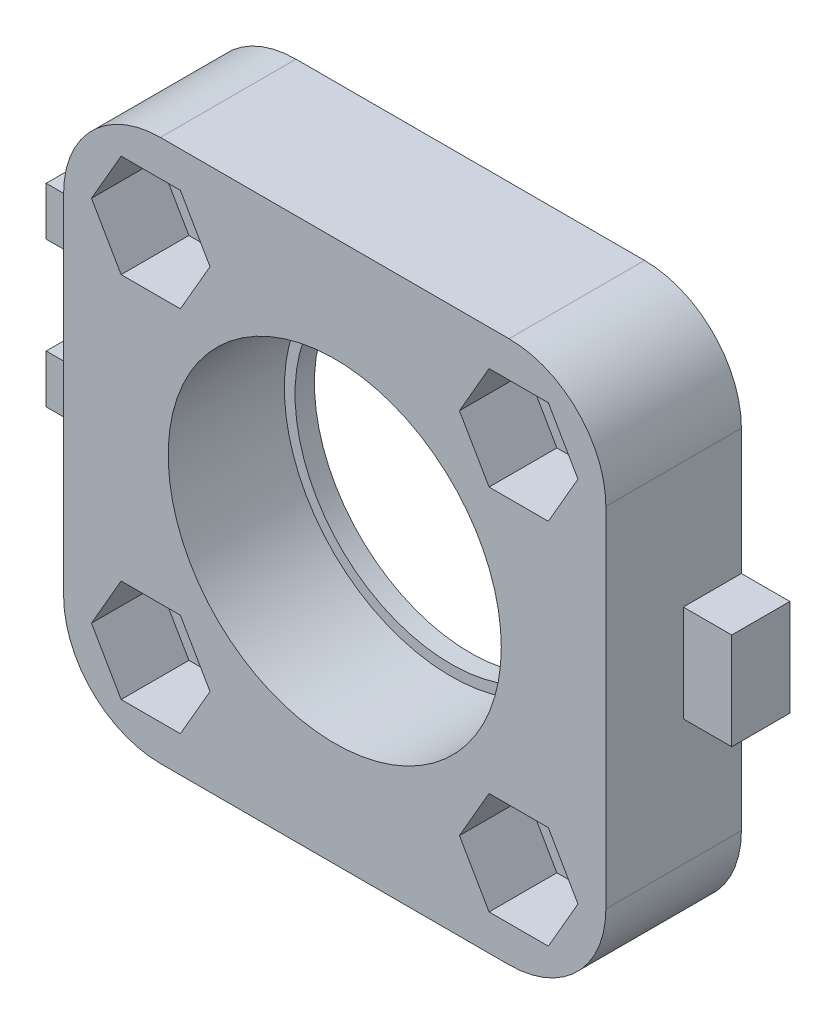
SolidWorks part; units mm, degrees
ref_plane "Alzado" through (0, 0, 0) normal (0, 0, 1) x (1, 0, 0)
ref_plane "Planta" through (0, 0, 0) normal (0, 1, 0) x (1, 0, 0)
ref_plane "Vista lateral" through (0, 0, 0) normal (1, 0, 0) x (0, 0, -1)
sketch "Croquis1" plane through (0, 0, 0) normal (0, 0, 1) x (1, 0, 0)
  line L1 (-14, -14) -> (14, -14)
  line L2 (-14, -14) -> (-14, 14)
  line L3 (-14, 14) -> (14, 14)
  line L4 (14, -14) -> (14, 14)
  line L5 (-14, -14) -> (14, 14) construction
  line L6 (-14, 14) -> (14, -14) construction
  circle A0 centre (0, 0) radius 8.05
  dimension "D1" = 16.1
  dimension "D2" = 28
  dimension "D3" = 28
extrude "Saliente-Extruir1" add sketch "Croquis1" along normal mid plane 1
sketch "Croquis2" plane through (0, 0, 0.5) normal (0, 0, 1) x (1, 0, 0)
  line L4 (14, -14) -> (14, 14)
  line L5 (14, 14) -> (-14, 14)
  line L6 (-14, 14) -> (-14, -14)
  line L7 (-14, -14) -> (14, -14)
  line L8 (14, -14) -> (14, 14)
  line L9 (14, 14) -> (-14, 14)
  line L10 (-14, 14) -> (-14, -14)
  line L11 (-14, -14) -> (14, -14)
  circle A0 centre (0, 0) radius 8.6
  dimension "D2" = 17.2
  dimension "D1" = 0
extrude "Saliente-Extruir2" add sketch "Croquis2" along normal blind 6
sketch "Croquis3" plane through (0, 0, 6.5) normal (0, 0, 1) x (1, 0, 0)
  line L0 (-9.5, 9.5) -> (9.5, 9.5) construction
  line L1 (9.5, 9.5) -> (9.5, -9.5) construction
  line L2 (9.5, -9.5) -> (-9.5, -9.5) construction
  line L3 (-9.5, -9.5) -> (-9.5, 9.5) construction
  line L5 (0, 13.0603) -> (0, -13.8489) construction
  line L6 (15.5492, 0) -> (-17.9148, 0) construction
  line L7 (11.03, 12.15) -> (7.97, 12.15)
  line L8 (-6.44, 9.5) -> (-7.97, 12.15)
  line L9 (-7.97, 12.15) -> (-11.03, 12.15)
  line L10 (-11.03, 12.15) -> (-12.56, 9.5)
  line L11 (-12.56, 9.5) -> (-11.03, 6.85)
  line L12 (-11.03, 6.85) -> (-7.97, 6.85)
  line L13 (-7.97, 6.85) -> (-6.44, 9.5)
  line L14 (7.97, 12.15) -> (6.44, 9.5)
  line L15 (6.44, 9.5) -> (7.97, 6.85)
  line L16 (7.97, 6.85) -> (11.03, 6.85)
  line L17 (11.03, 6.85) -> (12.56, 9.5)
  line L18 (12.56, 9.5) -> (11.03, 12.15)
  line L19 (-7.97, -6.85) -> (-11.03, -6.85)
  line L20 (-11.03, -6.85) -> (-12.56, -9.5)
  line L21 (-12.56, -9.5) -> (-11.03, -12.15)
  line L22 (-11.03, -12.15) -> (-7.97, -12.15)
  line L23 (-7.97, -12.15) -> (-6.44, -9.5)
  line L24 (-6.44, -9.5) -> (-7.97, -6.85)
  line L25 (11.03, -6.85) -> (7.97, -6.85)
  line L26 (7.97, -6.85) -> (6.44, -9.5)
  line L27 (6.44, -9.5) -> (7.97, -12.15)
  line L28 (7.97, -12.15) -> (11.03, -12.15)
  line L29 (11.03, -12.15) -> (12.56, -9.5)
  line L30 (12.56, -9.5) -> (11.03, -6.85)
  circle A0 centre (-9.5, 9.5) radius 1.5 construction
  circle A1 centre (-9.5, -9.5) radius 1.5 construction
  circle A2 centre (9.5, -9.5) radius 1.5 construction
  circle A3 centre (9.5, 9.5) radius 1.5 construction
  circle A4 centre (-9.5, 9.5) radius 2.65 construction
  circle A5 centre (9.5, 9.5) radius 2.65 construction
  circle A6 centre (-9.5, -9.5) radius 2.65 construction
  circle A7 centre (9.5, -9.5) radius 2.65 construction
  point P13 (0, -9.5)
  point P14 (-9.5, 0)
  dimension "D1" = 3
  dimension "D2" = 19
  dimension "D3" = 19
  dimension "D4" = 5.3
extrude "Cortar-Extruir1" cut sketch "Croquis3" against normal blind 3.5
sketch "Croquis6" plane through (0, 0, -0.5) normal (0, 0, -1) x (-1, 0, 0)
  line L0 (-9.5, 9.5) -> (9.5, 9.5) construction
  line L1 (9.5, 9.5) -> (9.5, -9.5) construction
  line L2 (9.5, -9.5) -> (-9.5, -9.5) construction
  line L3 (-9.5, -9.5) -> (-9.5, 9.5) construction
  line L4 (0, 17.9373) -> (0, -16.6332) construction
  line L5 (16.9599, 0) -> (-18.6245, 0) construction
  circle A0 centre (-9.5, 9.5) radius 1.5
  circle A1 centre (9.5, 9.5) radius 1.5
  circle A2 centre (9.5, -9.5) radius 1.5
  circle A3 centre (-9.5, -9.5) radius 1.5
  point P13 (0, 9.5)
  point P14 (-9.5, 0)
  dimension "D1" = 3
  dimension "D2" = 19
  dimension "D3" = 19
extrude "Cortar-Extruir2" cut sketch "Croquis6" against normal blind 23.5
sketch "Croquis7" plane through (0, 0, -0.5) normal (0, 0, -1) x (-1, 0, 0)
  line L0 (14, -14) -> (-14, -14) construction
  line L1 (-5, -14) -> (5, -14)
  line L2 (-5, -14) -> (-5, -17.5)
  line L3 (-5, -17.5) -> (5, -17.5)
  line L4 (5, -14) -> (5, -17.5)
  line L5 (-14, -14) -> (-14, 14) construction
  line L6 (-14, 2.5) -> (-16.5, 2.5)
  line L7 (-14, 2.5) -> (-14, -2.5)
  line L8 (-14, -2.5) -> (-16.5, -2.5)
  line L9 (-16.5, 2.5) -> (-16.5, -2.5)
  line L10 (14, 14) -> (14, -14) construction
  line L11 (14, 2.5) -> (16.5, 2.5)
  line L12 (14, 2.5) -> (14, -2.5)
  line L13 (14, -2.5) -> (16.5, -2.5)
  line L14 (16.5, 2.5) -> (16.5, -2.5)
  line L15 (0, 20.1506) -> (0, -30.1017) construction
  line L16 (-29.8997, 0) -> (35.1473, 0) construction
  line L17 (14, -5) -> (18.9, -5)
  line L18 (14, 2.5) -> (18.9, 2.5)
  line L19 (14, 2.5) -> (14, 5)
  line L20 (14, 5) -> (18.9, 5)
  line L21 (18.9, 2.5) -> (18.9, 5)
  line L22 (18.9, -2.5) -> (18.9, -5)
  line L23 (14, -2.5) -> (18.9, -2.5)
  line L24 (14, -2.5) -> (14, -5)
  point P23 (-16.5, 0)
  point P24 (16.5, 0)
  point P25 (0, -17.5)
  line M19 (-14, 14) -> (-14, -14)
  line M20 (-14, -14) -> (14, -14)
  line M21 (14, -14) -> (14, 14)
  dimension "D1" = 10
  dimension "D2" = 3.5
  dimension "D3" = 2.5
  dimension "D4" = 5
  dimension "D5" = 5
  dimension "D6" = 2.5
  dimension "D7" = 2.5
  dimension "D8" = 4.9
extrude "Saliente-Extruir3" add sketch "Croquis7" against normal blind 3 contours L6 L9 L8 M19 | L4 L2 L3 M20 | L23 L13 L17 L22 M21 | L14 L11 L13 M21 | L18 L21 L20 L11 M21
fillet "Redondeo1" radius 5 4 edges at (-14, -14, 3) (14, -14, 3) (14, 14, 3) (-14, 14, 3)
